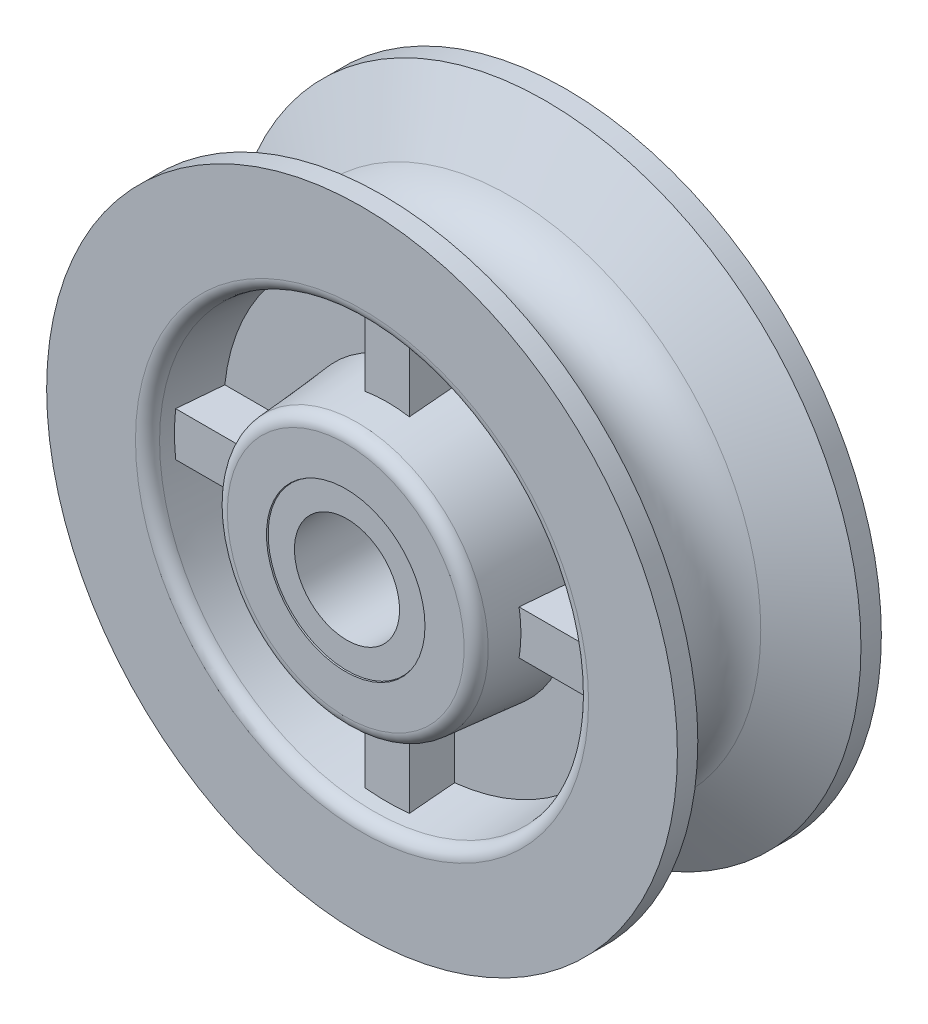
SolidWorks part; units mm, degrees
ref_plane "Front" through (0, 0, 0) normal (0, 0, 1) x (1, 0, 0)
ref_plane "Top" through (0, 0, 0) normal (0, 1, 0) x (1, 0, 0)
ref_plane "Right" through (0, 0, 0) normal (1, 0, 0) x (0, 0, -1)
sketch "Sketch1" plane through (0, 0, 0) normal (1, 0, 0) x (0, 0, -1)
  line L0 (4.9276, 19.05) -> (6.1595, 19.05)
  line L1 (-4.9276, 19.05) -> (-6.1595, 19.05)
  line L2 (-4.9276, 19.05) -> (-2.7837, 15.1417)
  line L3 (7.1438, 7.9375) -> (7.1438, 4.7625)
  line L4 (7.0676, 3.175) -> (-7.0675, 3.175)
  line L5 (-7.1437, 4.7625) -> (-7.1437, 7.9375)
  line L6 (4.9276, 19.05) -> (2.7837, 15.1417)
  line L8 (-7.1437, 0) -> (7.1437, 0) construction
  line L10 (6.1595, 19.05) -> (6.1595, 12.9857)
  line L12 (-7.1437, 4.7625) -> (-7.0675, 4.7625)
  line L13 (-7.0675, 4.7625) -> (-7.0675, 3.175)
  line L14 (0, 13.4937) -> (0, -13.4937) construction
  line L15 (7.0676, 4.7625) -> (7.1438, 4.7625)
  line L16 (7.0676, 4.7625) -> (7.0676, 3.175)
  line L17 (-6.1595, 19.05) -> (-6.1595, -19.05) construction
  line L18 (-6.1595, 12.9857) -> (-1.905, 12.9857)
  line L19 (-1.905, 12.9857) -> (-1.905, 7.9375)
  line L20 (-1.905, 7.9375) -> (-7.1437, 7.9375)
  line L21 (-6.1595, 12.9857) -> (-6.1595, 19.05)
  line L22 (6.1595, 12.9857) -> (1.905, 12.9857)
  line L23 (1.905, 12.9857) -> (1.905, 7.9375)
  line L24 (1.905, 7.9375) -> (7.1438, 7.9375)
  arc A0 (-2.7837, 15.1417) -> (2.7837, 15.1417) centre (0, 16.6687) ccw
  circle A1 centre (0, 16.6687) radius 3.175 construction
  circle A2 centre (0, 0) radius 3.175 construction
  circle A3 centre (0, 0) radius 4.7625 construction
  circle A4 centre (0, 0) radius 7.9375 construction
  circle A5 centre (0, -16.6687) radius 3.175 construction
  point P28 (-6.1595, 0)
  dimension "Rope Dia" = 6.35
  dimension "Shaft Dia" = 6.35
  dimension "D1" = 9.525
  dimension "D3" = 15.875
  dimension "Wd" = 14.2875
  dimension "D8" = 1.2319
  dimension "D9" = 0.0762
  dimension "Groove Dia" = 26.9875
  dimension "OD" = 38.1
  dimension "D2" = 3.81
  dimension "w Wd" = 12.319
  dimension "D4" = 0.508
revolve "Revolve1" add sketch "Sketch1" angle 360 about L8
sketch "Sketch2" plane through (0, 0, 0) normal (0, 0, 1) x (1, 0, 0)
  circle A0 centre (0, 0) radius 4.7625 construction
  circle A1 centre (0, 0) radius 4.7625
extrude "Cut-Extrude-Thin1" cut sketch "Sketch2" against normal through all and the other way through all thin
draft "Draft1" type of draft neutral plane draft angle 5 faces to draft 2 face at (7.9375, 0, 7.1437) face at (12.9857, 0, 1.905) neutral plane through (0, 12.9857, 6.1595) neutral plane normal (0, 0, 1) parameters "D1"=5
draft "Draft2" type of draft neutral plane draft angle 15 faces to draft 2 face at (7.9375, 0, -1.905) face at (12.9857, 0, -6.1595) neutral plane through (0, 19.05, -6.1595) neutral plane normal (0, 0, -1) parameters "D1"=15
fillet "Fillet1" radius 0.762 4 edges at (12.9857, 0, 6.1595) (12.9857, 0, -6.1595) (-7.8514, 0, 7.1437) (7.6738, 0, -7.1438)
sketch "Sketch4" plane through (0, 0, 0) normal (0, 0, 1) x (1, 0, 0)
  line L0 (0, 12.9857) -> (0, 4.7625)
extrude "Extrude-Thin1" add sketch "Sketch4" along normal offset from surface 1.524 and the other way offset from surface (4.6355 mm away) 1.524 thin up to face at (-13.684, 0, 6.1595) other way up to face at (13.5705, 0, -6.1595) thin type mid plane wall 2.667
pattern_circular "CirPattern1" count 4 over 360 about axis through (0, 0, 0) along (0, 0, 1) of "Extrude-Thin1"
equation "\"D1@Sketch1\" = \"Shaft Dia@Sketch1\" * 1.5"
equation "\"D3@Sketch1\" = \"Shaft Dia@Sketch1\" * 2.5"
equation "\"D5@Extrude-Thin1\" = \"OD@Sketch1\" * .07"
